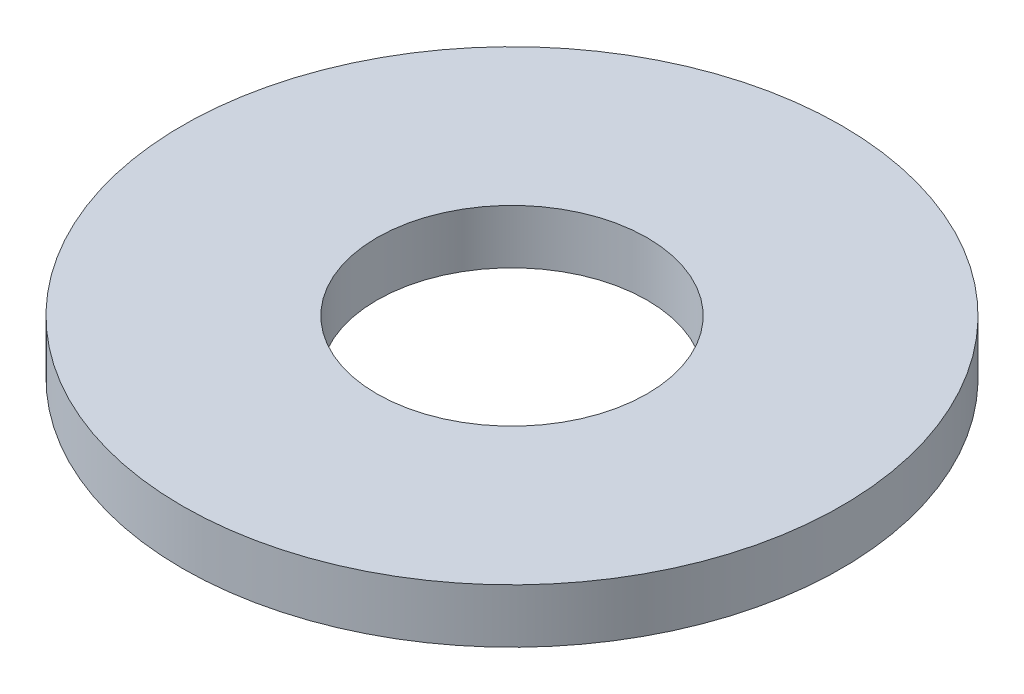
SolidWorks part; units mm, degrees
material "炭素鋼(普通)"
ref_plane "正面" through (0, 0, 0) normal (0, 0, 1) x (1, 0, 0)
ref_plane "平面" through (0, 0, 0) normal (0, 1, 0) x (1, 0, 0)
ref_plane "右側面" through (0, 0, 0) normal (1, 0, 0) x (0, 0, -1)
sketch "ｽｹｯﾁ1" plane through (0, 0, 0) normal (0, 1, 0) x (1, 0, 0)
  circle A0 centre (0, 0) radius 4.875
  circle A1 centre (0, 0) radius 2
  dimension "D1" = 9.75
  dimension "D2" = 4
extrude "ﾎﾞｽ - 押し出し1" add sketch "ｽｹｯﾁ1" along normal blind 0.8
